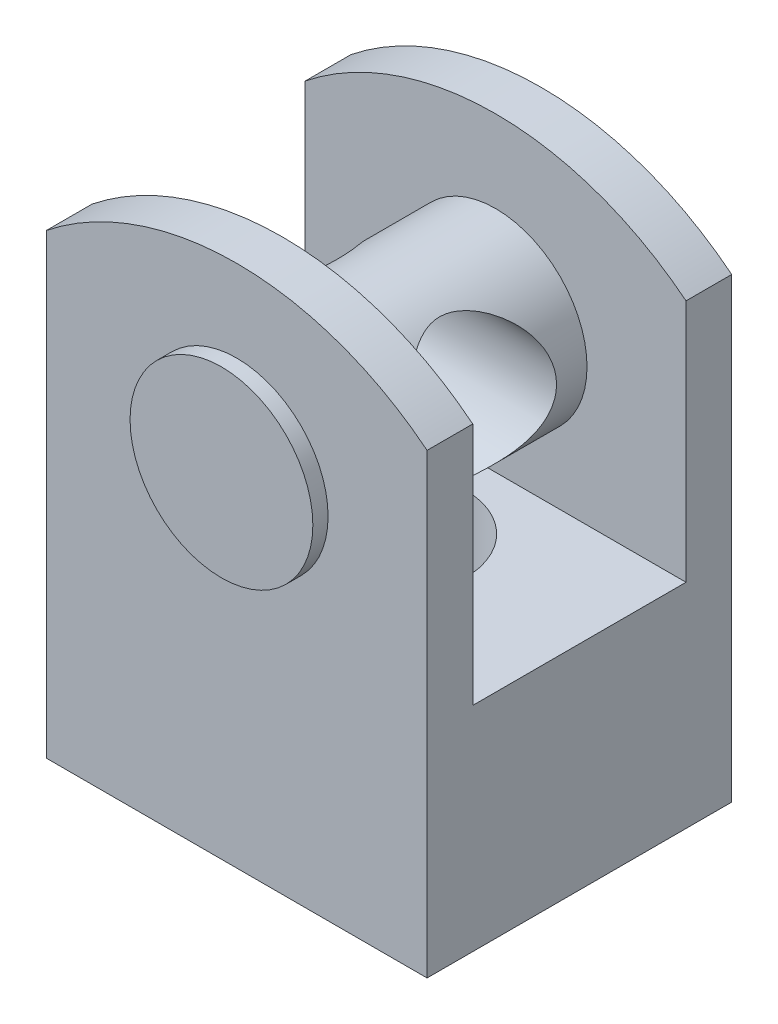
SolidWorks part; units mm, degrees
ref_plane "Front Plane" through (0, 0, 0) normal (0, 0, 1) x (1, 0, 0)
ref_plane "Top Plane" through (0, 0, 0) normal (0, 1, 0) x (1, 0, 0)
ref_plane "Right Plane" through (0, 0, 0) normal (1, 0, 0) x (0, 0, -1)
sketch "Sketch1" plane through (0, 0, 0) normal (0, 0, 1) x (1, 0, 0)
  line L0 (-12.5, 15) -> (-12.5, -15)
  line L1 (-12.5, -15) -> (12.5, -15)
  line L2 (12.5, -15) -> (12.5, 15)
  arc A0 (-12.5, 15) -> (12.5, 15) centre (0, -0.6125) cw
  circle A1 centre (0, 8) radius 5
  point P2 (0, -15)
  point P5 (12.5, 0)
  point P7 (-12.5, 0)
  dimension "D3" = 20
  dimension "D4" = 7
  dimension "D1" = 30
  dimension "D2" = 25
extrude "Boss-Extrude1" add sketch "Sketch1" along normal mid plane 20
sketch "Sketch2" plane through (12.5, 0, 0) normal (1, 0, 0) x (0, 0, -1)
  line L0 (0, -1) -> (-7, -1)
  line L1 (-7, -1) -> (-7, 28.0135)
  line L2 (-7, 28.0135) -> (7, 28.0135)
  line L3 (7, 28.0135) -> (7, -1)
  line L4 (7, -1) -> (0, -1)
  dimension "D4" = 16
  dimension "D1" = 14
  dimension "D2" = 7
  dimension "D3" = 3
extrude "Cut-Extrude1" cut sketch "Sketch2" against normal through all both and the other way through all
sketch "Sketch4" plane through (0, 0, 10) normal (0, 0, 1) x (1, 0, 0)
  circle A0 centre (0, 8) radius 6
  dimension "D1" = 12
extrude "Boss-Extrude2" add sketch "Sketch4" along normal blind 1 and the other way blind 21
sketch "Sketch5" plane through (0, 0, 0) normal (1, 0, 0) x (0, 0, -1)
  circle A0 centre (0, 8) radius 5
extrude "Cut-Extrude3" cut sketch "Sketch5" against normal mid plane 15
sketch "Sketch6" plane through (0, -15, 0) normal (0, -1, 0) x (1, 0, 0)
  circle A0 centre (0, 0) radius 5
  dimension "D1" = 10
extrude "Cut-Extrude4" cut sketch "Sketch6" against normal blind 15
